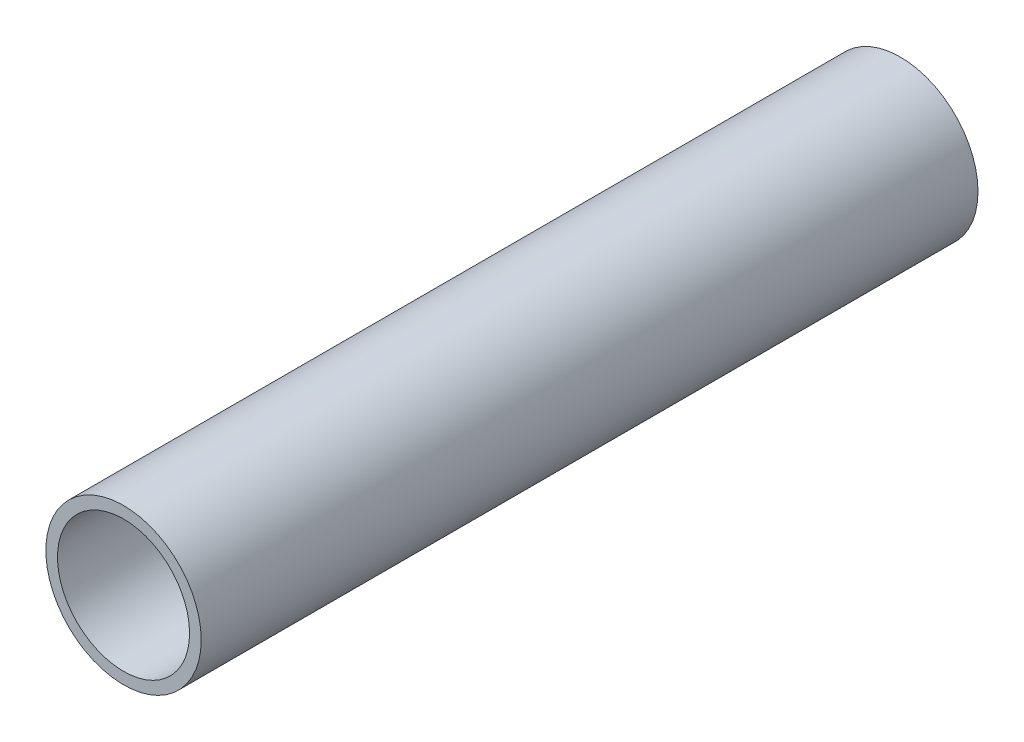
SolidWorks part; units mm, degrees
material "PE Высокой плотности"
ref_plane "Front" through (0, 0, 0) normal (0, 0, 1) x (1, 0, 0)
ref_plane "Top" through (0, 0, 0) normal (0, 1, 0) x (1, 0, 0)
ref_plane "Side" through (0, 0, 0) normal (1, 0, 0) x (0, 0, -1)
sketch "PipeSketch" plane through (0, 0, 0) normal (0, 0, 1) x (1, 0, 0)
  circle A0 centre (0, 0) radius 10
  circle A1 centre (0, 0) radius 8.5
  dimension "OuterDiameter" = 20
  dimension "InnerDiameter" = 17
extrude "Extrusion" add sketch "PipeSketch" along normal blind 100
sketch "FilterSketch" plane through (0, 0, 0) normal (0, 0, 1) x (1, 0, 0)
  circle A0 centre (0, 0) radius 10 construction
  dimension "NominalDiameter" = 20
